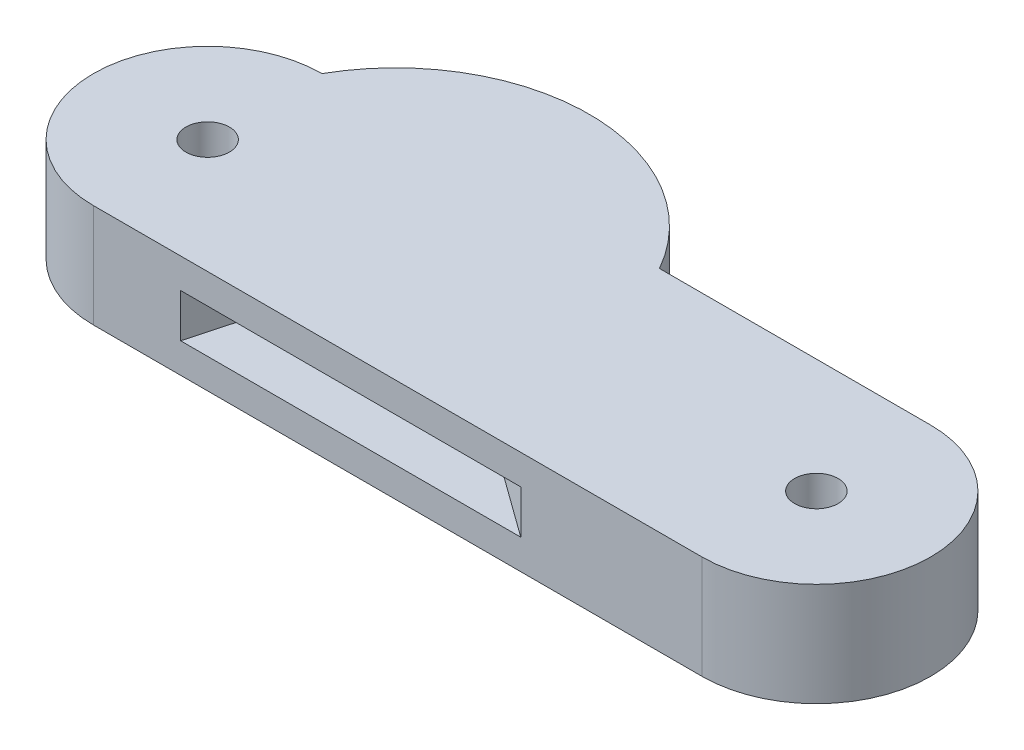
SolidWorks part; units mm, degrees
ref_plane "Front Plane" through (0, 0, 0) normal (0, 0, 1) x (1, 0, 0)
ref_plane "Top Plane" through (0, 0, 0) normal (0, 1, 0) x (1, 0, 0)
ref_plane "Right Plane" through (0, 0, 0) normal (1, 0, 0) x (0, 0, -1)
sketch "Sketch1" plane through (0, 0, 0) normal (0, 1, 0) x (1, 0, 0)
  line L0 (0, -10.5004) -> (-55.9305, -10.5004)
  line L1 (0, 10.5004) -> (-55.9305, 10.5004)
  line L5 (0, 11.5004) -> (-55.9305, 11.5004) construction
  line L6 (0, -11.5004) -> (-55.9305, -11.5004) construction
  circle A0 centre (0, 0) radius 2
  arc A1 (0, -10.5004) -> (0, 10.5004) centre (0, 0) ccw
  arc A2 (-55.9305, 10.5004) -> (-55.9305, -10.5004) centre (-55.9305, 0) ccw
  circle A3 centre (-55.9305, 0) radius 2
  arc A7 (0, -11.5004) -> (0, 11.5004) centre (0, 0) ccw construction
  arc A8 (-55.9305, 11.5004) -> (-55.9305, -11.5004) centre (-55.9305, 0) ccw construction
  arc A9 (-67.2423, -5.04) -> (-54.9145, -15.6487) centre (-55.7741, -4.1805) ccw construction
  arc A10 (-55.9305, 10.5004) -> (-55.9305, -10.5004) centre (-55.9305, 0) ccw construction
  circle A11 centre (0, 0) radius 67.4309 construction
  arc A12 (-59.8966, 30.973) -> (-67.2423, -5.04) centre (0, 0) ccw construction
  dimension "D1" = 4
  dimension "D2" = 1
  dimension "D3" = 4
extrude "Boss-Extrude1" add sketch "Sketch1" along normal mid plane 9.5
sketch "Sketch3" plane through (0, 0, 0) normal (0, 1, 0) x (1, 0, 0)
  line L0 (0, 0) -> (-47.1525, -15.3208) construction
  line L1 (0, 0) -> (24.7895, -42.9367) construction
  line L2 (0, 0) -> (-55.9305, 0) construction
  line L3 (24.7895, -42.9367) -> (-41.5934, 5.0595) construction
  line L4 (-41.5934, 5.0595) -> (-47.1525, -15.3208) construction
  line L5 (-41.5934, 5.0595) -> (-37.6461, 19.5308) construction
  line L6 (-41.5934, 5.0595) -> (-53.749, 13.8482) construction
  line L7 (22.8477, -44.0007) -> (-38.0092, 0) construction
  line L8 (-35.7518, 18.8753) -> (-39.2995, 5.869)
  line L9 (-43.8873, 4.25) -> (-54.8123, 12.149)
  line L11 (26.6452, -41.8104) -> (-39.2995, 5.869)
  line L12 (-39.6108, 19.9279) -> (-42.7627, 8.3729) construction
  line L13 (-42.7627, 8.3729) -> (-52.4686, 15.3905) construction
  line L14 (-40.9004, 0) -> (-45.9674, -18.5763) construction
  line L15 (-43.8873, 4.25) -> (-48.2065, -11.585)
  line L18 (-40.4216, 6.6802) -> (-50.8477, 14.2185) construction
  line L20 (-41.5934, 5.0595) -> (-52.0196, 12.5978) construction
  line L21 (-42.7652, 3.4387) -> (-53.1914, 10.977) construction
  line L23 (-43.5229, 5.5858) -> (-49.082, -14.7945) construction
  line L26 (-39.6639, 4.5332) -> (-45.223, -15.8471) construction
  line L27 (25.9613, -41.316) -> (-40.4216, 6.6802) construction
  line L28 (23.6177, -44.5574) -> (-42.7652, 3.4387) construction
  arc A1 (-48.2065, -11.585) -> (26.6452, -41.8104) centre (0, 0) ccw
  arc A4 (-55.9305, 10.5004) -> (-55.9305, -10.5004) centre (-55.9305, 0) ccw construction
  arc A7 (-35.7518, 18.8753) -> (-54.8123, 12.149) centre (-41.5934, 5.0595) ccw
  dimension "D1" = 99.1581
  dimension "D3" = 120
  dimension "D6" = 30
  dimension "D2" = 18
  dimension "D4" = 2
  dimension "D5" = 2
extrude "Cut-Extrude1" cut sketch "Sketch3" against normal mid plane 4
sketch "Sketch5" plane through (0, 0, 0) normal (0, 1, 0) x (1, 0, 0)
  line L0 (-40.4241, 1.7461) -> (-52.5322, 10.5004) construction
  line L1 (-40.4241, 1.7461) -> (-35.7382, 18.9254) construction
  line L2 (-52.5322, 10.5004) -> (-43.8873, 4.25) construction
  line L3 (-39.2995, 5.869) -> (-38.0362, 10.5004) construction
  line L4 (-55.9305, 10.5004) -> (-24.9177, 10.5004)
  line L5 (0, 10.5004) -> (-55.9305, 10.5004) construction
  circle A0 centre (-40.4241, 1.7461) radius 17.807
extrude "Boss-Extrude2" add sketch "Sketch5" along normal up to surface and the other way up to surface
sketch "Sketch6" plane through (0, 0, 0) normal (0, 1, 0) x (1, 0, 0)
  line L0 (-39.2995, 5.869) -> (-16.6593, -10.5004)
  line L1 (-47.9107, -10.5004) -> (-43.8873, 4.25)
  line L2 (-43.8873, 4.25) -> (-54.8544, 12.1794)
  line L3 (-39.2995, 5.869) -> (-35.7382, 18.9254)
  line L4 (-16.6593, -10.5004) -> (-39.2995, 5.869) construction
  line L5 (-43.8873, 4.25) -> (-47.9107, -10.5004) construction
  line L6 (-52.5322, 10.5004) -> (-43.8873, 4.25) construction
  line L7 (-39.2995, 5.869) -> (-38.0362, 10.5004) construction
  line L8 (-55.9305, -10.5004) -> (0, -10.5004) construction
  line L9 (-16.6593, -10.5004) -> (-47.9107, -10.5004)
  arc A0 (-24.9177, 10.5004) -> (-55.9305, 10.5004) centre (-40.4241, 1.7461) ccw construction
  arc A1 (-35.7382, 18.9254) -> (-54.8544, 12.1794) centre (-40.4241, 1.7461) ccw
extrude "Cut-Extrude2" cut sketch "Sketch6" against normal mid plane 4
